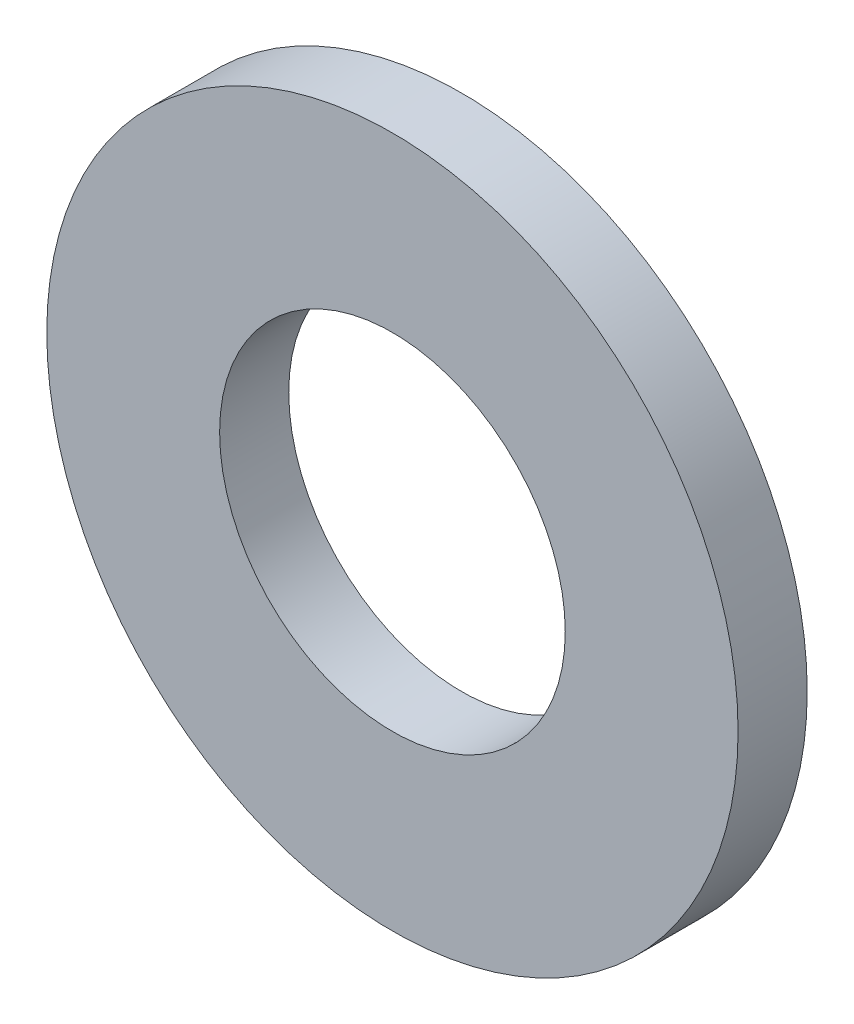
SolidWorks part; units mm, degrees
ref_plane "Front Plane" through (0, 0, 0) normal (0, 0, 1) x (1, 0, 0)
ref_plane "Top Plane" through (0, 0, 0) normal (0, 1, 0) x (1, 0, 0)
ref_plane "Right Plane" through (0, 0, 0) normal (1, 0, 0) x (0, 0, -1)
sketch "Sketch1" plane through (0, 0, 0) normal (0, 0, 1) x (1, 0, 0)
  circle A0 centre (0, 0) radius 7.9375
  circle A1 centre (0, 0) radius 3.9688
  dimension "D1" = 15.875
  dimension "ID" = 7.9375
extrude "Extrude1" add sketch "Sketch1" along normal mid plane 1.5875
sketch "Sketch2" plane through (0, 0, 0) normal (1, 0, 0) x (0, 0, -1)
  line L0 (-0.7937, -3.9688) -> (0.7937, -3.9688) construction
  line L3 (0.7937, 3.9688) -> (-0.7937, 3.9688) construction
  line L5 (-0.7937, -3.9688) -> (0.7937, -3.9688)
  line L6 (0.7937, 3.9688) -> (-0.7937, 3.9688)
sketch "Sketch4" plane through (0, 0, 0.7937) normal (0, 0, 1) x (1, 0, 0)
  line L0 (0, 0) -> (-2.8063, 2.8063)
  line L1 (0, -1.7463) -> (0, 1.7463) construction
  circle A0 centre (0, 0) radius 3.9688 construction
  dimension "D1" = 45
